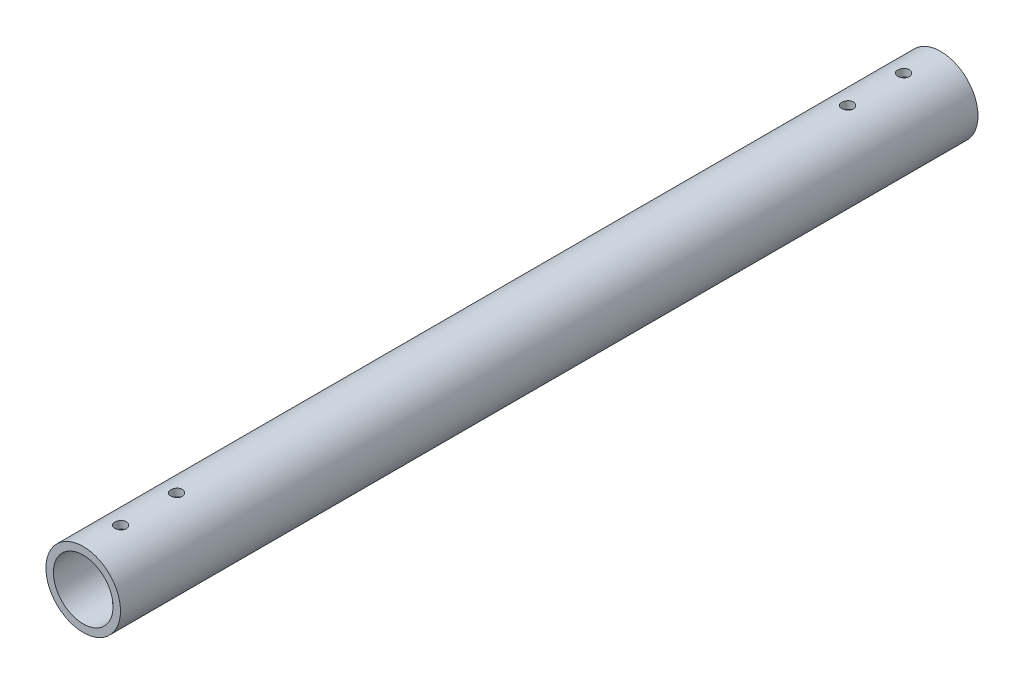
SolidWorks part; units mm, degrees
material "Thornel Mat VMA"
ref_plane "前视基准面" through (0, 0, 0) normal (0, 0, 1) x (1, 0, 0)
ref_plane "上视基准面" through (0, 0, 0) normal (0, 1, 0) x (1, 0, 0)
ref_plane "右视基准面" through (0, 0, 0) normal (1, 0, 0) x (0, 0, -1)
other "Configuration Table"
sketch "草图1" plane through (0, 0, 0) normal (0, 0, 1) x (1, 0, 0)
  circle A0 centre (0, 0) radius 10
  circle A2 centre (0, 0) radius 8
  dimension "D1" = 20
  dimension "D2" = 16
extrude "凸台-拉伸1" add sketch "草图1" along normal blind 230
sketch "草图2" plane through (0, 0, 0) normal (0, 1, 0) x (1, 0, 0)
  line L1 (-10, -230) -> (10, -230) construction
  line L2 (-0.1962, 0) -> (0, 0)
  line L3 (10, 0) -> (-10, 0) construction
  line L4 (0, 0) -> (0, -230) construction
  circle A0 centre (0, -10) radius 1.55
  circle A1 centre (0, -25) radius 1.55
  circle A2 centre (0, -220) radius 1.55
  circle A3 centre (0, -205) radius 1.55
  dimension "D1" = 3.1
  dimension "D2" = 3.1
  dimension "D5" = 3.1
  dimension "D6" = 3.1
  dimension "D3" = 10
  dimension "D4" = 15
  dimension "D7" = 10
  dimension "D8" = 15
extrude "切除-拉伸1" cut sketch "草图2" against normal blind 230 and the other way through all contours A0 | A1 | A2 | A3
